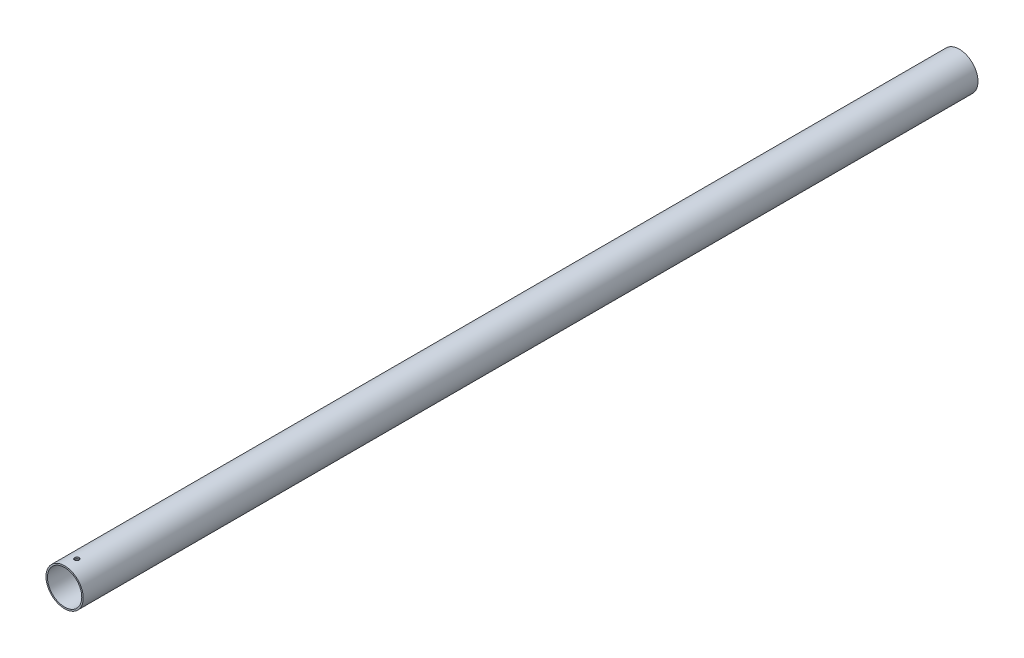
SolidWorks part; units mm, degrees
ref_plane "Plan de face" through (0, 0, 0) normal (0, 0, 1) x (1, 0, 0)
ref_plane "Plan de dessus" through (0, 0, 0) normal (0, 1, 0) x (1, 0, 0)
ref_plane "Plan de droite" through (0, 0, 0) normal (1, 0, 0) x (0, 0, -1)
sketch "Esquisse1" plane through (0, 0, 0) normal (0, 0, 1) x (1, 0, 0)
  circle A0 centre (0, 0) radius 11.5
  circle A1 centre (0, 0) radius 12.5
  dimension "D1" = 25
  dimension "D2" = 23
extrude "Boss.-Extru.1" add sketch "Esquisse1" along normal blind 600
sketch "Esquisse2" plane through (0, 0, 0) normal (0, 1, 0) x (1, 0, 0)
  circle A0 centre (0, -591.85) radius 1.5
  dimension "D1" = 3
extrude "Enlèv. mat.-Extru.1" cut sketch "Esquisse2" along normal through all
